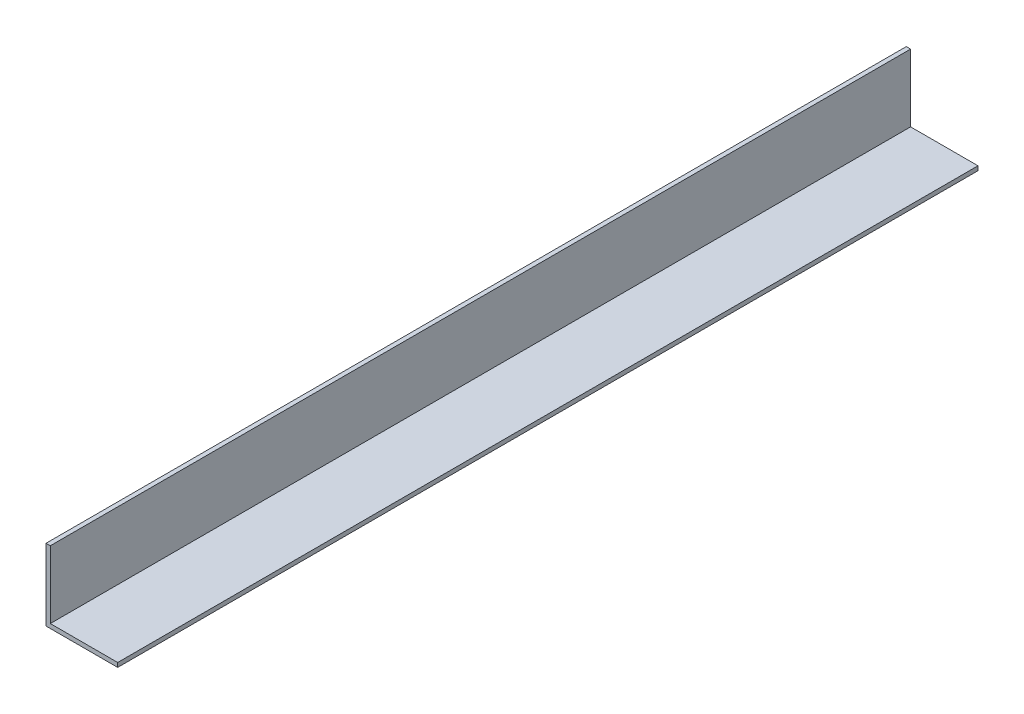
SolidWorks part; units mm, degrees
ref_plane "Front Plane" through (0, 0, 0) normal (0, 0, 1) x (1, 0, 0)
ref_plane "Top Plane" through (0, 0, 0) normal (0, 1, 0) x (1, 0, 0)
ref_plane "Right Plane" through (0, 0, 0) normal (1, 0, 0) x (0, 0, -1)
sketch "Sketch1" plane through (0, 0, 0) normal (0, 0, 1) x (1, 0, 0)
  line L0 (0, 0) -> (0, 25)
  line L1 (0, 25) -> (1.5, 25)
  line L2 (1.5, 25) -> (1.5, 1.5)
  line L3 (1.5, 1.5) -> (25, 1.5)
  line L4 (25, 1.5) -> (25, 0)
  line L5 (25, 0) -> (0, 0)
  dimension "D1" = 1.5
  dimension "D2" = 25
extrude "Boss-Extrude1" add sketch "Sketch1" along normal blind 300
